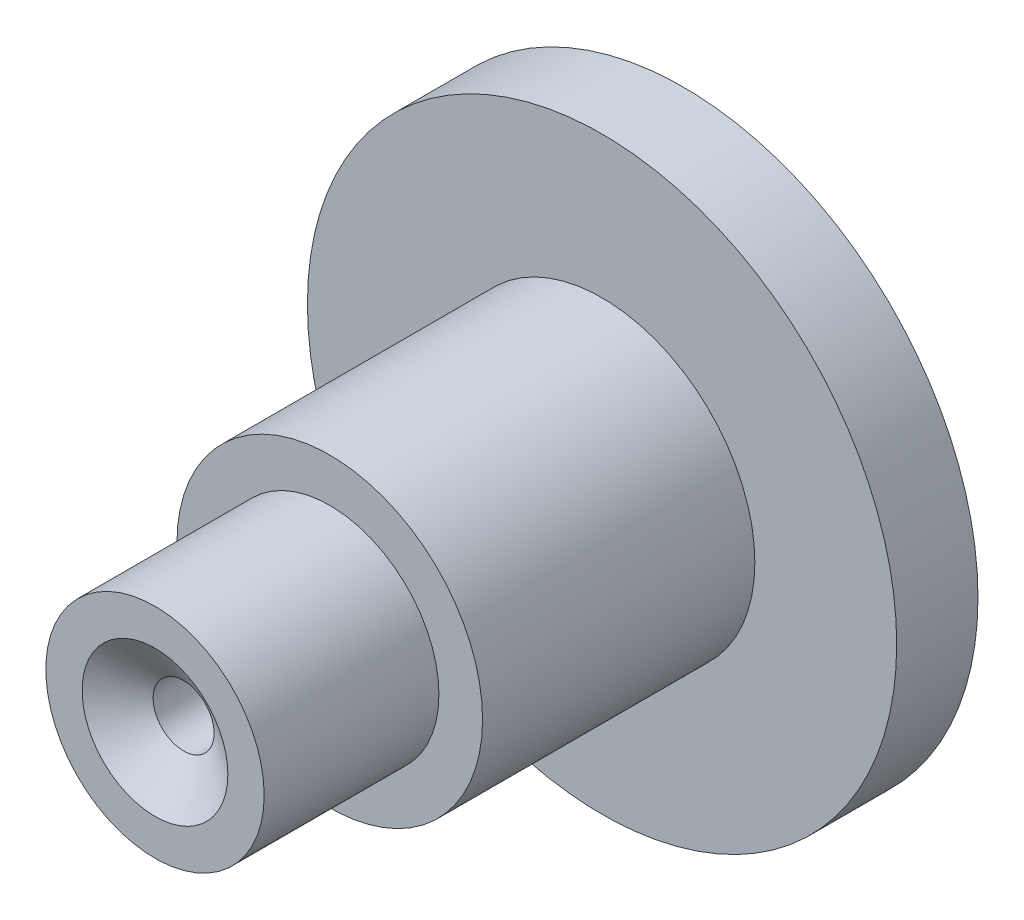
SolidWorks part; units mm, degrees
ref_plane "Front Plane" through (0, 0, 0) normal (0, 0, 1) x (1, 0, 0)
ref_plane "Top Plane" through (0, 0, 0) normal (0, 1, 0) x (1, 0, 0)
ref_plane "Right Plane" through (0, 0, 0) normal (1, 0, 0) x (0, 0, -1)
sketch "Sketch1" plane through (0, 0, 0) normal (1, 0, 0) x (0, 0, -1)
  line L0 (0, 0) -> (0, 46.0375)
  line L1 (0, 46.0375) -> (-12.7, 46.0375)
  line L2 (-12.7, 46.0375) -> (-12.7, 23.876)
  line L3 (-12.7, 23.876) -> (-55.245, 23.876)
  line L4 (-55.245, 23.876) -> (-55.245, 17.0595)
  line L5 (-55.245, 17.0595) -> (-82.55, 17.0595)
  line L7 (-78.0777, 4.7625) -> (-57.15, 4.7625)
  line L8 (-57.15, 4.7625) -> (-57.15, 0)
  line L9 (-57.15, 0) -> (0, 0)
  line L10 (-82.55, 17.0595) -> (-82.55, 11.3858)
  line L11 (-82.55, 11.3858) -> (-78.0777, 4.7625)
  dimension "D1" = 46.0375
  dimension "D2" = 69.85
  dimension "D3" = 23.876
  dimension "D4" = 12.7
  dimension "D5" = 4.7625
  dimension "D6" = 42.545
  dimension "D7" = 25.4
revolve "Revolve1" add sketch "Sketch1" angle 360 about L9
